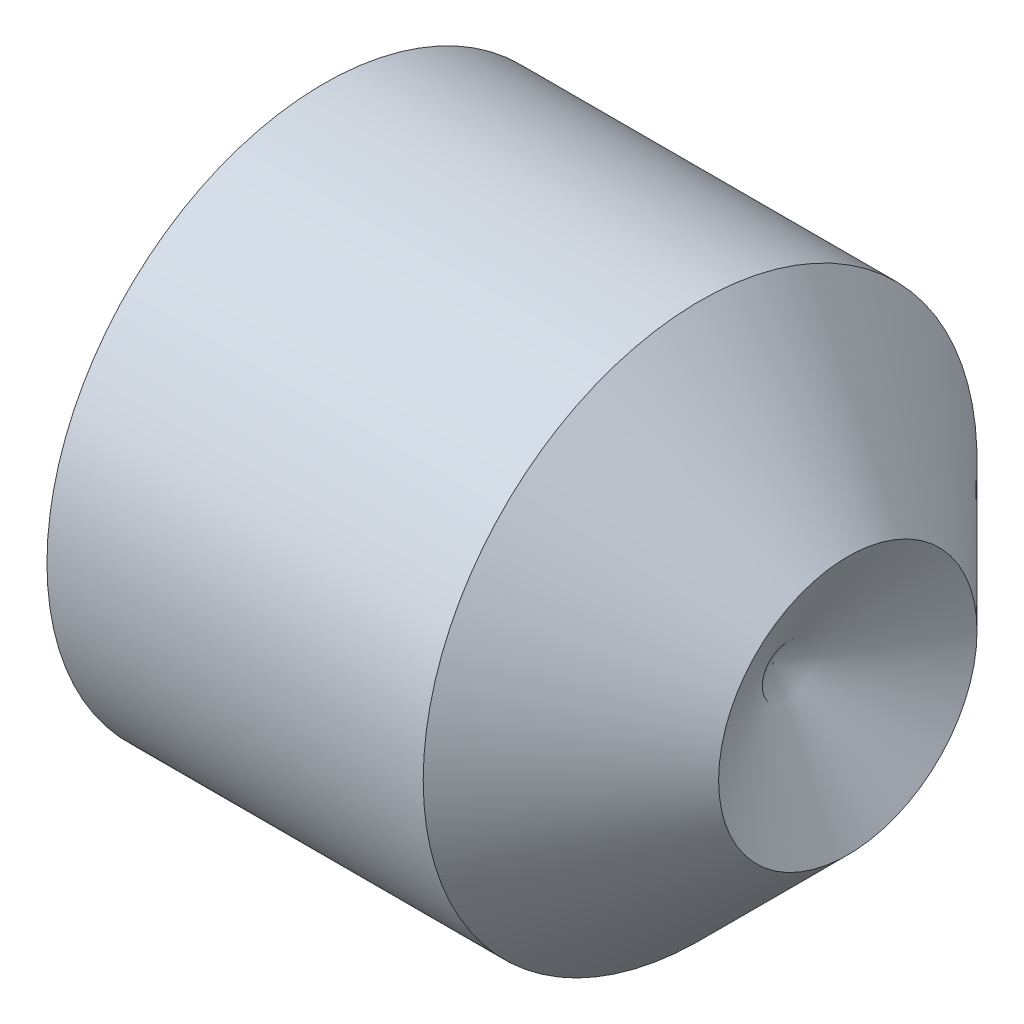
SolidWorks part; units mm, degrees
revolve "BaseBody" add sketch "BodySke" angle 360 about L5
sketch "BodySke" plane through (0, 0, 0) normal (0, 0, 1) x (1, 0, 0)
  line L0 (0, 0) -> (0, 1.2195)
  line L1 (0, 1.2195) -> (0.1619, 1.5)
  line L2 (0.1619, 1.5) -> (2.2, 1.5)
  line L3 (2.2, 1.5) -> (3, 0.7)
  line L4 (2.5959, 0) -> (0, 0)
  line L5 (-12.7, 0) -> (88.9, 0) construction
  line L6 (2.5959, 0) -> (3, 0.7)
  line L7 (3, 0.7) -> (3, 10.225) construction
  line L8 (0, -1.2195) -> (0.1619, -1.5) construction
  line L9 (2.5959, 0) -> (3, -0.7) construction
  line L10 (2.2, -1.5) -> (3, -0.7) construction
  line L11 (0.25, 15.875) -> (0.25, -3.175) construction
  dimension "Diameter" = 3
  dimension "Drive_ch_ang" = 60
  dimension "Minor_dia" = 2.439
  dimension "Cup_ang" = 120
  dimension "Cup_dia" = 1.4
  dimension "Length" = 3
  dimension "Cup_nose_ang" = 45
  dimension "Advance" = 0.5
cosmetic thread "ThreadCosmetic" parameters "Thread_minor"=2.439
ref_plane "Plane1" through (0, 0, 0) normal (0, 0, 1) x (1, 0, 0)
ref_plane "Plane2" through (0, 0, 0) normal (0, 1, 0) x (1, 0, 0)
ref_plane "Plane3" through (0, 0, 0) normal (1, 0, 0) x (0, 0, -1)
sketch "Sketch2" plane through (0, 0, 0) normal (-1, 0, 0) x (0, 0, 1)
  line L0 (0.433, 0.75) -> (-0.433, 0.75)
  line L1 (-0.433, 0.75) -> (-0.866, 0)
  line L2 (0.433, 0.75) -> (0.866, 0)
  line L3 (0.433, -0.75) -> (0.866, 0)
  line L4 (0.433, -0.75) -> (-0.433, -0.75)
  line L5 (-0.433, -0.75) -> (-0.866, 0)
  dimension "Hex_size" = 1.5
  dimension "D2" = 0.75
  dimension "D3" = 0.75
extrude "Hex" cut sketch "Sketch2" against normal blind 1.2
sketch "ThdSchSke" plane through (0, 0, 0) normal (0, 0, 1) x (1, 0, 0)
  line L0 (0.1619, -1.2195) -> (-0.0345, -1.5)
  line L1 (0.1619, -1.2195) -> (0.3584, -1.5)
  line L2 (0.3584, -1.5) -> (0.3584, -1.875)
  line L3 (-3.175, 0) -> (5.1513, 0) construction
  line L4 (0.1619, 1.5) -> (0.1619, -1.5) construction
  line L5 (0.3584, -1.875) -> (-0.0345, -1.875)
  line L6 (-0.0345, -1.875) -> (-0.0345, -1.5)
  dimension "Thread_minor" = 2.439
  dimension "Diameter" = 3
revolve "ThreadSchematic" [suppressed] cut sketch "ThdSchSke" angle 360 about L3
pattern_linear "ThdSchPat" [suppressed]
equation "\"D2@Sketch2\" = \"Hex_size@Sketch2\" / 2"
equation "\"D3@Sketch2\" = \"Hex_size@Sketch2\" / 2"
equation "\"Thread_minor@ThreadCosmetic\" = \"Minor_dia@BodySke\""
equation "\"Thread_minor@ThdSchSke\" = \"Thread_minor@ThreadCosmetic\""
equation "\"Diameter@ThdSchSke\" = \"Diameter@BodySke\""
equation "\"Overcut@ThdSchSke\" = \"Diameter@BodySke\" * 1.25"
equation "\"Num_threads@ThdSchPat\" = int( (\"Length@BodySke\" - ( ( ( \"Diameter@BodySke\" - \"Minor_dia@BodySke\" ) * 0.5 ) / tan( \"Drive_ch_ang@BodySke\" * 0.017453292 ) ) - ( ( ( \"Diameter@BodySke\" - \"Cup_dia@BodySke\" ) * 0.5 ) * tan( \"Cup_nose_ang@BodySke\" * 0.017453292 ) ) ) / \"Advance@BodySke\" + 0.999 )  + 1"
equation "\"Advance@ThdSchPat\" = (\"Length@BodySke\" - ( ( ( \"Diameter@BodySke\" - \"Minor_dia@BodySke\" ) * 0.5 ) / tan( \"Drive_ch_ang@BodySke\" * 0.017453292 ) ) - ( ( ( \"Diameter@BodySke\" - \"Cup_dia@BodySke\" ) * 0.5 ) * tan( \"Cup_nose_ang@BodySke\" * 0.017453292 ) ) ) /  (\"Num_threads@ThdSchPat\" - 1) 'relax it"
equation "' \"Num_threads@ThdSchPat\" = \"Num_threads@ThdSchPat\" - sgn( \"Num_threads@ThdSchPat\" - 1) '---chamfered tips only---"
